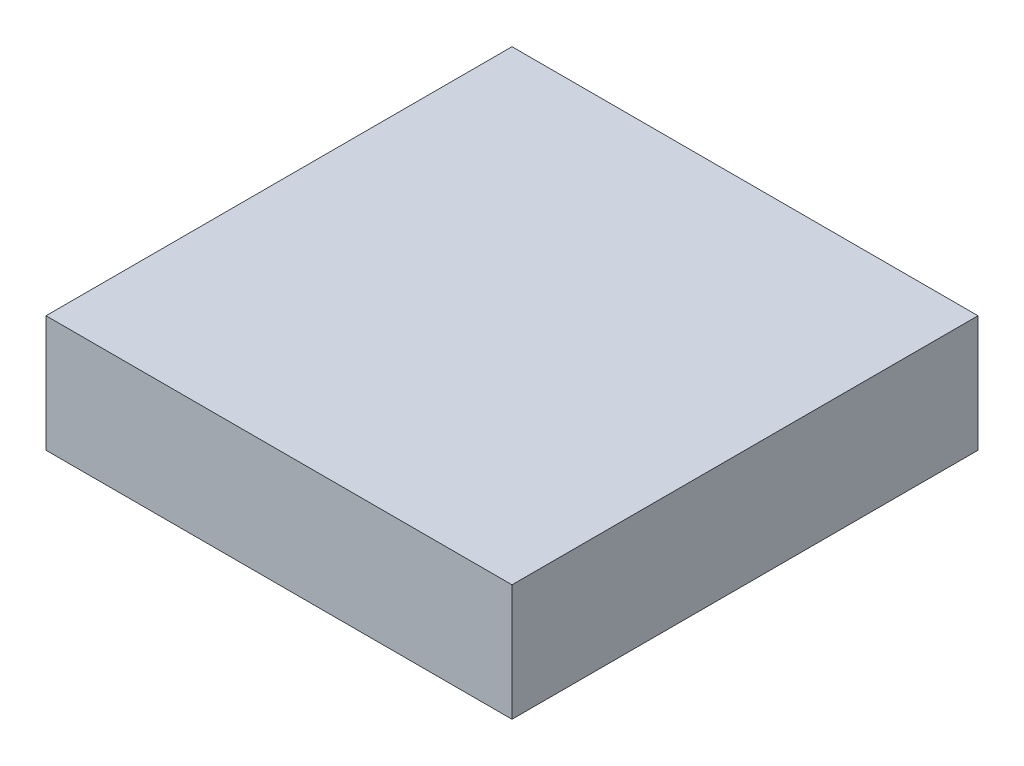
SolidWorks part; units mm, degrees
ref_plane "Front Plane" through (0, 0, 0) normal (0, 0, 1) x (1, 0, 0)
ref_plane "Top Plane" through (0, 0, 0) normal (0, 1, 0) x (1, 0, 0)
ref_plane "Right Plane" through (0, 0, 0) normal (1, 0, 0) x (0, 0, -1)
sketch "Sketch1" plane through (0, 0, 0) normal (0, 1, 0) x (1, 0, 0)
  line L1 (0, 0) -> (60, 0)
  line L2 (0, 0) -> (0, 60)
  line L3 (0, 60) -> (60, 60)
  line L4 (60, 0) -> (60, 60)
  point P6 (0, 0)
extrude "Boss-Extrude1" add sketch "Sketch1" along normal blind 15 contours L1 L4 L3 L2
